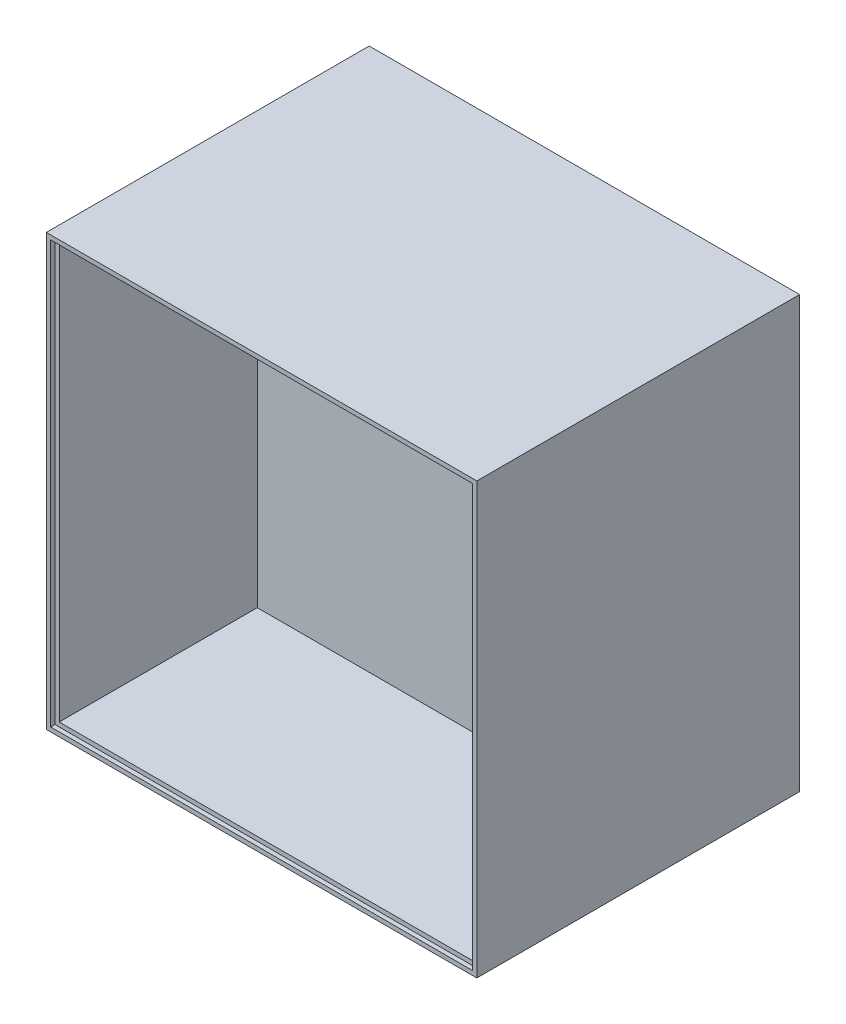
SolidWorks part; units mm, degrees
ref_plane "Front Plane" through (0, 0, 0) normal (0, 0, 1) x (1, 0, 0)
ref_plane "Top Plane" through (0, 0, 0) normal (0, 1, 0) x (1, 0, 0)
ref_plane "Right Plane" through (0, 0, 0) normal (1, 0, 0) x (0, 0, -1)
sketch "Sketch4" plane through (0, 0, 0) normal (0, 0, 1) x (1, 0, 0)
  line L1 (0, 0) -> (200, 0)
  line L2 (0, 0) -> (0, 200)
  line L3 (0, 200) -> (200, 200)
  line L4 (200, 0) -> (200, 200)
  dimension "D1" = 200
  dimension "D2" = 200
extrude "Boss-Extrude1" add sketch "Sketch4" along normal blind 150 contours L2 L1 L4 L3
sketch "Sketch5" plane through (0, 0, 150) normal (0, 0, 1) x (1, 0, 0)
  line L0 (100, 0) -> (100, 2) construction
  line L1 (0, 0) -> (200, 0) construction
  line L2 (0, 100) -> (2, 100) construction
  line L6 (200, 100) -> (198, 100) construction
  line L7 (200, 0) -> (200, 200) construction
  line L8 (100, 200) -> (100, 198) construction
  line L9 (0, 200) -> (200, 200) construction
  line L10 (100, 198) -> (198, 198) construction
  line L11 (198, 198) -> (198, 100) construction
  line L12 (0, 0) -> (0, 200) construction
  line L13 (2, 100) -> (198, 100)
  point P11 (0, 100)
  point P14 (0, 100)
  dimension "D1" = 2
  dimension "D2" = 2
  dimension "D3" = 2
  dimension "D4" = 2
sketch "Sketch6" plane through (0, 0, 150) normal (0, 0, 1) x (1, 0, 0)
  line L0 (2, 100) -> (198, 100) construction
  line L1 (2, 2) -> (198, 2)
  line L2 (2, 2) -> (2, 198)
  line L3 (2, 198) -> (198, 198)
  line L4 (198, 2) -> (198, 198)
  line L5 (2, 2) -> (198, 198) construction
  line L6 (2, 198) -> (198, 2) construction
  point P0 (100, 100)
extrude "Cut-Extrude1" cut sketch "Sketch6" against normal blind 2 contours L2 L1 L4 L3
sketch "Sketch7" plane through (0, 0, 148) normal (0, 0, 1) x (1, 0, 0)
  line L0 (100, 198) -> (100, 196) construction
  line L1 (2, 100) -> (4, 100) construction
  line L2 (2, 100) -> (198, 100) construction
  line L3 (198, 100) -> (196, 100) construction
  line L4 (100, 2) -> (100, 4) construction
  line L6 (4, 4) -> (196, 4)
  line L7 (4, 4) -> (4, 196)
  line L8 (4, 196) -> (196, 196)
  line L9 (196, 4) -> (196, 196)
  line L10 (4, 4) -> (196, 196) construction
  line L11 (4, 196) -> (196, 4) construction
  point P14 (100, 100)
  dimension "D1" = 2
  dimension "D2" = 2
  dimension "D3" = 2
  dimension "D4" = 2
extrude "Cut-Extrude2" cut sketch "Sketch7" against normal blind 92
sketch "Sketch9" plane through (200, 0, 0) normal (1, 0, 0) x (0, 0, -1)
  line L0 (-150, 100) -> (0, 100) construction
  line L1 (-150, 0) -> (-150, 200) construction
  line L2 (0, 0) -> (0, 200) construction
  line L3 (-75, 200) -> (-75, 0) construction
  line L4 (-150, 0) -> (0, 0) construction
  line L5 (0, 0) -> (0, 4) construction
  line L6 (0, 0) -> (-4, 0) construction
  line L7 (-4, 0) -> (-4, 4) construction
  line L8 (-4, 4) -> (0, 4) construction
  line L9 (-4, 4) -> (-150, 4) construction
  line L10 (-75, 0) -> (-75, 4) construction
  line L11 (-150, 200) -> (0, 200) construction
  line L12 (-75, 4) -> (-47, 4)
  line L13 (-75, 4) -> (-75, 50.8)
  line L14 (-75, 50.8) -> (-47, 50.8)
  line L15 (-47, 4) -> (-47, 50.8)
  dimension "D1" = 4
  dimension "D2" = 4
  dimension "D3" = 28
  dimension "D4" = 46.8
sketch "Sketch11" plane through (0, 0, 0) normal (-1, 0, 0) x (0, 0, 1)
  line L0 (75, 0) -> (75, 200) construction
  line L2 (150, 0) -> (0, 0) construction
  line L3 (150, 200) -> (0, 200) construction
  line L5 (150, 0) -> (150, 200) construction
  line L6 (75, 0) -> (75, 4) construction
  line L7 (150, 100) -> (146, 100) construction
  line L10 (75, 4) -> (150, 4) construction
  line L11 (146, 100) -> (146, 4) construction
  line L12 (75, 100) -> (150, 100) construction
  line L13 (99.9, 64.4) -> (125.1, 64.4)
  line L14 (99.9, 64.4) -> (99.9, 135.6)
  line L15 (99.9, 135.6) -> (125.1, 135.6)
  line L16 (125.1, 64.4) -> (125.1, 135.6)
  line L17 (99.9, 64.4) -> (125.1, 135.6) construction
  line L18 (99.9, 135.6) -> (125.1, 64.4) construction
  line L19 (94.5, 60) -> (130.5, 60)
  line L20 (94.5, 60) -> (94.5, 140)
  line L21 (94.5, 140) -> (130.5, 140)
  line L22 (130.5, 60) -> (130.5, 140)
  line L23 (94.5, 60) -> (130.5, 140) construction
  line L24 (94.5, 140) -> (130.5, 60) construction
  line L25 (97, 62.5) -> (128, 62.5)
  line L26 (97, 62.5) -> (97, 137.5)
  line L27 (97, 137.5) -> (128, 137.5)
  line L28 (128, 62.5) -> (128, 137.5)
  line L29 (97, 62.5) -> (128, 137.5) construction
  line L30 (97, 137.5) -> (128, 62.5) construction
  circle A0 centre (128, 137.5) radius 1.25
  circle A1 centre (97, 137.5) radius 1.25
  circle A2 centre (97, 62.5) radius 1.25
  circle A3 centre (128, 62.5) radius 1.25
  point P8 (112.5, 100)
  point P19 (112.5, 100)
  point P24 (112.5, 100)
  dimension "D1" = 4
  dimension "D2" = 4
  dimension "D9" = 2.5
  dimension "D10" = 2.5
  dimension "D11" = 2.5
  dimension "D12" = 2.5
  dimension "D3" = 25.2
  dimension "D4" = 71.2
  dimension "D5" = 36
  dimension "D6" = 80
  dimension "D7" = 75
  dimension "D8" = 31
sketch "Sketch12" plane through (0, 0, 0) normal (-1, 0, 0) x (0, 0, 1)
  line L0 (75, 200) -> (75, 0) construction
  line L1 (150, 200) -> (0, 200) construction
  line L2 (150, 0) -> (0, 0) construction
  line L3 (75, 100) -> (0, 100) construction
  line L4 (150, 0) -> (150, 200) construction
  line L5 (0, 0) -> (0, 200) construction
  line L6 (0, 200) -> (4, 200) construction
  line L7 (0, 200) -> (0, 196) construction
  line L8 (4, 200) -> (4, 0) construction
  line L9 (0, 196) -> (150, 196) construction
  line L10 (37.5, 100) -> (37.5, 196) construction
  line L11 (37.5, 100) -> (37.5, 0) construction
  circle A0 centre (37.5, 100) radius 0.55
  circle A1 centre (37.5, 80) radius 0.55
  circle A2 centre (37.5, 60) radius 0.55
  circle A3 centre (37.5, 148) radius 1
  dimension "D1" = 4
  dimension "D2" = 4
  dimension "D3" = 1.1
  dimension "D5" = 2
  dimension "D4" = 3
sketch "Sketch13" plane through (200, 0, 0) normal (1, 0, 0) x (0, 0, -1)
  line L0 (-4, 4) -> (-4, 200) construction
  line L1 (-150, 200) -> (0, 200) construction
  line L2 (-75, 200) -> (-75, 196) construction
  line L3 (-75, 200) -> (-75, 0) construction
  line L4 (-150, 100) -> (-146, 100) construction
  line L5 (-150, 100) -> (0, 100) construction
  line L6 (-4, 196) -> (-146, 196) construction
  line L7 (-146, 196) -> (-146, 4) construction
  line L8 (-4, 4) -> (-150, 4) construction
  line L9 (-4, 196) -> (-4, 192) construction
  line L10 (-4, 196) -> (-8, 196) construction
  line L11 (-8, 196) -> (-8, 192) construction
  line L12 (-8, 192) -> (-4, 192) construction
  line L13 (-75, 100) -> (-75, 60) construction
  line L14 (-75, 60) -> (-4, 60) construction
  line L15 (-146, 196) -> (-142, 196) construction
  line L16 (-8, 192) -> (-12, 192)
  line L17 (-8, 192) -> (-8, 60)
  line L18 (-8, 60) -> (-12, 60)
  line L19 (-12, 192) -> (-12, 60)
  line L20 (-146, 196) -> (-146, 192) construction
  line L21 (-142, 196) -> (-142, 192) construction
  line L22 (-142, 192) -> (-146, 192) construction
  line L23 (-18, 192) -> (-18, 60)
  line L24 (-18, 192) -> (-22, 192)
  line L25 (-22, 192) -> (-22, 60)
  line L26 (-18, 60) -> (-22, 60)
  line L27 (-28, 192) -> (-28, 60)
  line L28 (-28, 192) -> (-32, 192)
  line L29 (-32, 192) -> (-32, 60)
  line L30 (-28, 60) -> (-32, 60)
  line L31 (-38, 192) -> (-38, 60)
  line L32 (-38, 192) -> (-42, 192)
  line L33 (-42, 192) -> (-42, 60)
  line L34 (-38, 60) -> (-42, 60)
  line L35 (-48, 192) -> (-48, 60)
  line L36 (-48, 192) -> (-52, 192)
  line L37 (-52, 192) -> (-52, 60)
  line L38 (-48, 60) -> (-52, 60)
  line L39 (-58, 192) -> (-58, 60)
  line L40 (-58, 192) -> (-62, 192)
  line L41 (-62, 192) -> (-62, 60)
  line L42 (-58, 60) -> (-62, 60)
  line L43 (-68, 192) -> (-68, 60)
  line L44 (-68, 192) -> (-72, 192)
  line L45 (-72, 192) -> (-72, 60)
  line L46 (-68, 60) -> (-72, 60)
  line L47 (-78, 192) -> (-78, 60)
  line L48 (-78, 192) -> (-82, 192)
  line L49 (-82, 192) -> (-82, 60)
  line L50 (-78, 60) -> (-82, 60)
  line L51 (-88, 192) -> (-88, 60)
  line L52 (-88, 192) -> (-92, 192)
  line L53 (-92, 192) -> (-92, 60)
  line L54 (-88, 60) -> (-92, 60)
  line L55 (-98, 192) -> (-98, 60)
  line L56 (-98, 192) -> (-102, 192)
  line L57 (-102, 192) -> (-102, 60)
  line L58 (-98, 60) -> (-102, 60)
  line L59 (-108, 192) -> (-108, 60)
  line L60 (-108, 192) -> (-112, 192)
  line L61 (-112, 192) -> (-112, 60)
  line L62 (-108, 60) -> (-112, 60)
  line L63 (-118, 192) -> (-118, 60)
  line L64 (-118, 192) -> (-122, 192)
  line L65 (-122, 192) -> (-122, 60)
  line L66 (-118, 60) -> (-122, 60)
  line L67 (-128, 192) -> (-128, 60)
  line L68 (-128, 192) -> (-132, 192)
  line L69 (-132, 192) -> (-132, 60)
  line L70 (-128, 60) -> (-132, 60)
  line L71 (-138, 192) -> (-138, 60)
  line L72 (-138, 192) -> (-142, 192)
  line L73 (-142, 192) -> (-142, 60)
  line L74 (-138, 60) -> (-142, 60)
  dimension "D1" = 4
  dimension "D2" = 4
  dimension "D3" = 4
  dimension "D4" = 4
  dimension "D5" = 40
  dimension "D6" = 4
  dimension "D7" = 4
  dimension "D8" = 14
equation "\"L\"= 100mm"
equation "\"T\"= 1mm"
equation "\"D1@Sketch4\"=2*\"L\""
equation "\"D2@Sketch4\"=2*\"L\""
equation "\"D1@Boss-Extrude1\"=1.5*\"L\""
equation "\"D1@Sketch5\"=(1/50)*\"L\""
equation "\"D2@Sketch5\"=(1/50)*\"L\""
equation "\"D3@Sketch5\"=(1/50)*\"L\""
equation "\"D4@Sketch5\"=(1/50)*\"L\""
equation "\"D1@Cut-Extrude1\"=(1/50)*\"L\""
equation "\"D1@Sketch7\"=(1/50)*\"L\""
equation "\"D2@Sketch7\"=(1/50)*\"L\""
equation "\"D3@Sketch7\"=(1/50)*\"L\""
equation "\"D4@Sketch7\"=(1/50)*\"L\""
equation "\"D1@Sketch9\"=4*\"T\""
equation "\"D2@Sketch9\"=4*\"T\""
equation "\"D3@Sketch9\"=(7/25)*\"L\""
equation "\"D4@Sketch9\"=(46.8/100)*\"L\""
equation "\"D1@Sketch11\"=4*\"T\""
equation "\"D2@Sketch11\"=4*\"T\""
equation "\"D3@Sketch11\"=(25.2/100)*\"L\""
equation "\"D4@Sketch11\"=(71.2/100)*\"L\""
equation "\"D5@Sketch11\"=(9/25)*\"L\""
equation "\"D6@Sketch11\"=(4/5)*\"L\""
equation "\"D7@Sketch11\"=(3/4)*\"L\""
equation "\"D8@Sketch11\"=(31/100)*\"L\""
equation "\"D9@Sketch11\"=(1/40)*\"L\""
equation "\"D10@Sketch11\"=(1/40)*\"L\""
equation "\"D11@Sketch11\"=(1/40)*\"L\""
equation "\"D12@Sketch11\"=(1/40)*\"L\""
equation "\"D1@Sketch12\"=4*\"T\""
equation "\"D2@Sketch12\"=4*\"T\""
equation "\"D3@Sketch12\"=(1.1/100)*\"L\""
equation "\"D5@Sketch12\"=(1/50)*\"L\""
equation "\"D1@Sketch13\"=4*\"T\""
equation "\"D2@Sketch13\"=4*\"T\""
equation "\"D3@Sketch13\"=4*\"T\""
equation "\"D4@Sketch13\"=4*\"T\""
equation "\"D5@Sketch13\"=(2/5)*\"L\""
equation "\"D6@Sketch13\"=4*\"T\""
equation "\"D7@Sketch13\"=4*\"T\""
